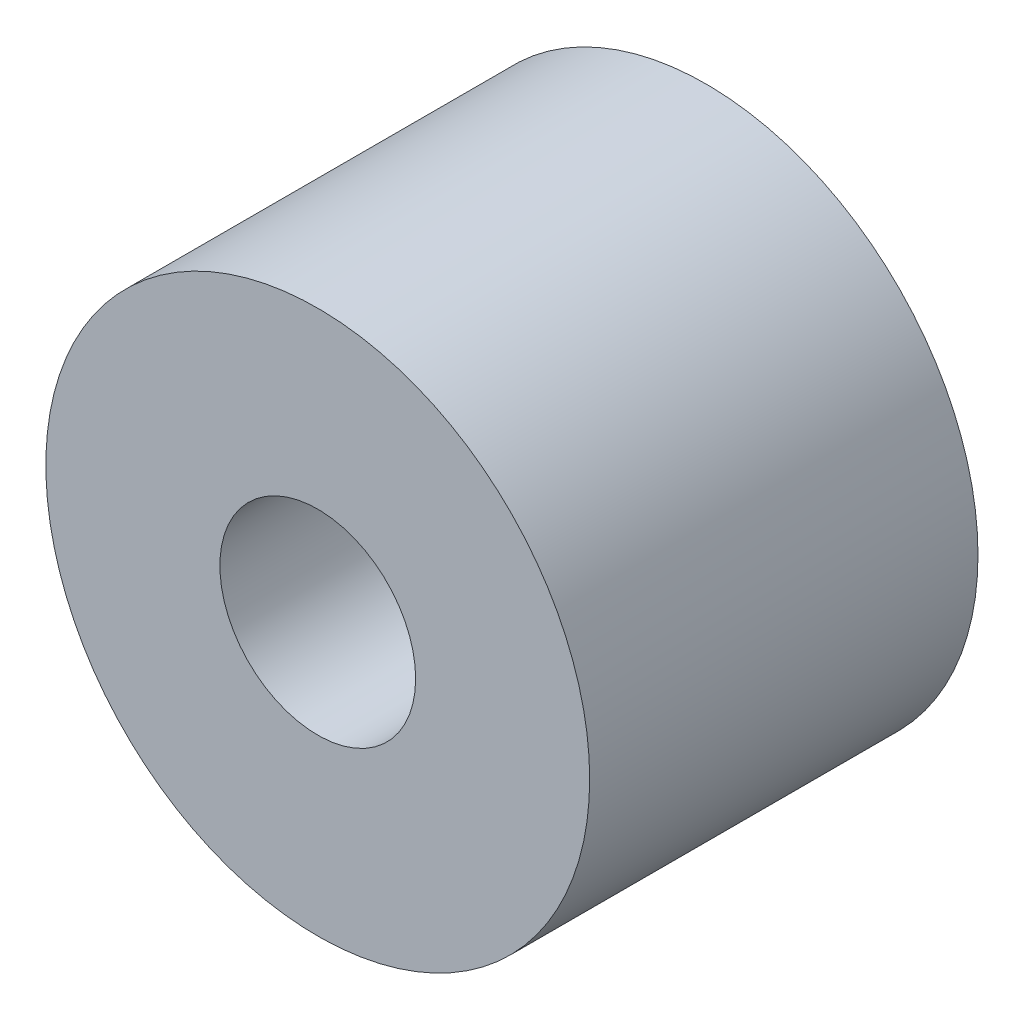
SolidWorks part; units mm, degrees
material "6061-T6 (SS)"
ref_plane "Front Plane" through (0, 0, 0) normal (0, 0, 1) x (1, 0, 0)
ref_plane "Top Plane" through (0, 0, 0) normal (0, 1, 0) x (1, 0, 0)
ref_plane "Right Plane" through (0, 0, 0) normal (1, 0, 0) x (0, 0, -1)
sketch "Sketch1" plane through (0, 0, 0) normal (0, 0, 1) x (1, 0, 0)
  circle A0 centre (0, 0) radius 2.286
  circle A1 centre (0, 0) radius 6.35
  dimension "D1" = 4.572
  dimension "D2" = 12.7
extrude "Boss-Extrude1" add sketch "Sketch1" along normal blind 9.0678
